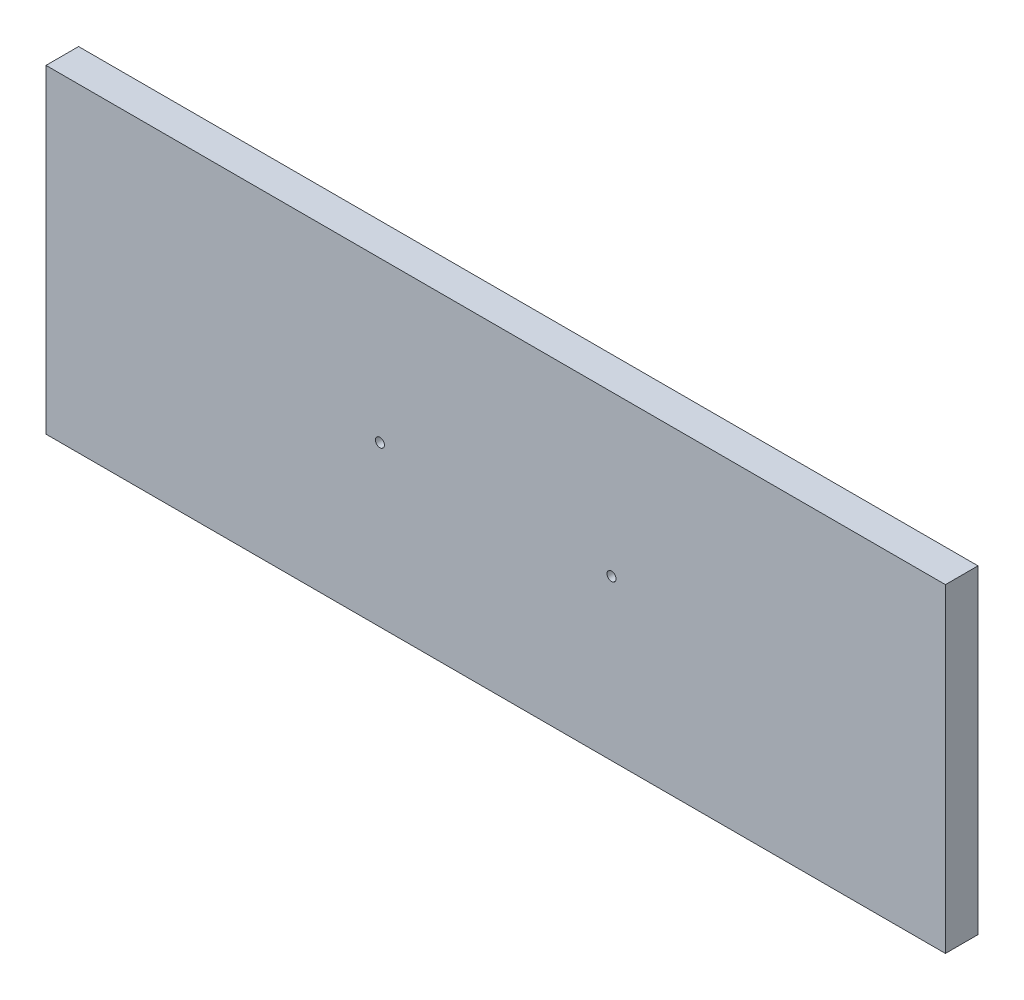
SolidWorks part; units mm, degrees
ref_plane "Front Plane" through (0, 0, 0) normal (0, 0, 1) x (1, 0, 0)
ref_plane "Top Plane" through (0, 0, 0) normal (0, 1, 0) x (1, 0, 0)
ref_plane "Right Plane" through (0, 0, 0) normal (1, 0, 0) x (0, 0, -1)
sketch "Sketch1" plane through (0, 0, 0) normal (0, 0, 1) x (1, 0, 0)
  line L0 (248.5, -214.5) -> (-248.5, -214.5) construction
  line L1 (-248.5, -391) -> (-248.5, -214.5) construction
  line L2 (248.5, -391) -> (-248.5, -391) construction
  line L3 (248.5, -391) -> (248.5, -214.5) construction
  line L4 (248.5, -214.5) -> (-248.5, -214.5)
  line L5 (-248.5, -391) -> (-248.5, -214.5)
  line L6 (248.5, -391) -> (-248.5, -391)
  line L7 (248.5, -391) -> (248.5, -214.5)
  dimension "D1" = 497
  dimension "D2" = 176.5
extrude "Boss-Extrude1" add sketch "Sketch1" along normal blind 18
extrude "Cut-Extrude4" cut sketch "Sketch5" against normal blind 18
sketch "Sketch5" plane through (0, 0, 18) normal (0, 0, 1) x (1, 0, 0)
  line L0 (0, -214.5) -> (0, -391) construction
  circle A0 centre (64, -302.75) radius 2.5
  circle A1 centre (-64, -302.75) radius 2.5
extrude "Cut-Extrude5" cut sketch "Sketch6" against normal blind 12
sketch "Sketch6" plane through (0, 0, 0) normal (0, 0, -1) x (-1, 0, 0)
  line L0 (0, -214.5) -> (0, -391) construction
  circle A0 centre (224, -270.5) radius 5
  circle A1 centre (-224, -270.5) radius 5
  circle A2 centre (224, -334.5) radius 5
  circle A3 centre (-224, -334.5) radius 5
  point P16 (216.5, -375)
